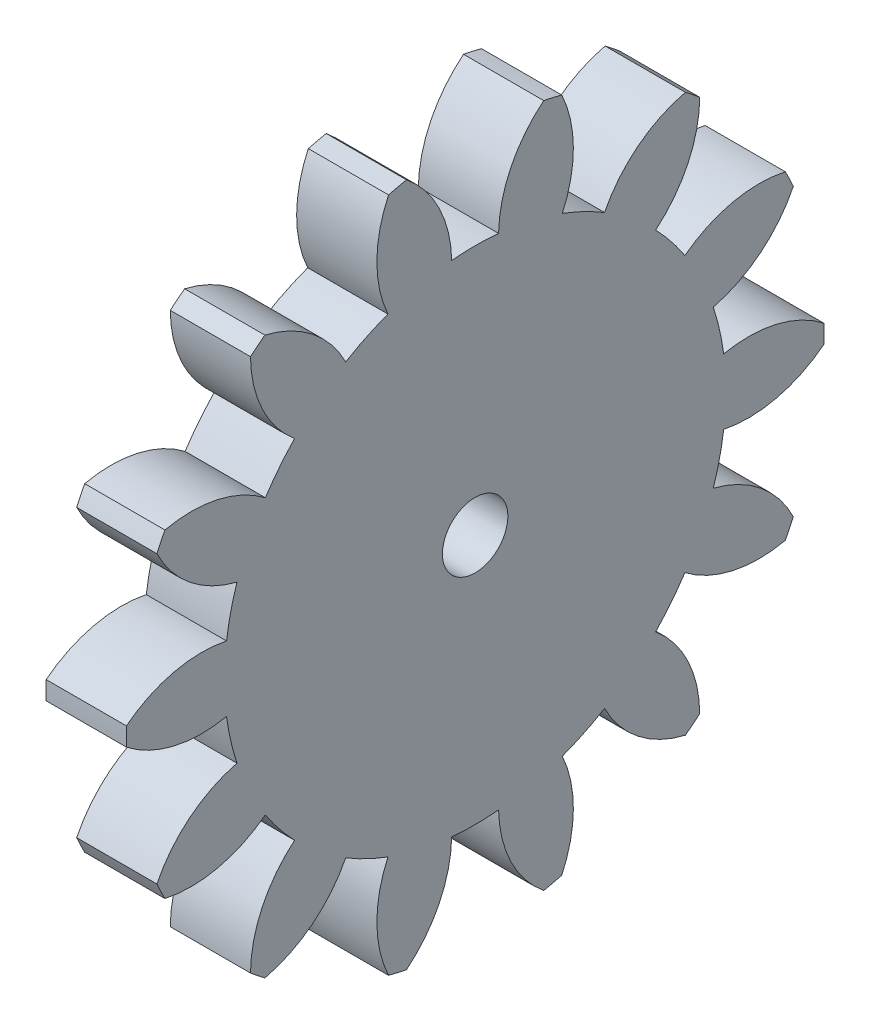
SolidWorks part; units mm, degrees
ref_plane "Plane1" through (0, 0, 0) normal (0, 0, 1) x (1, 0, 0)
ref_plane "Plane2" through (0, 0, 0) normal (0, 1, 0) x (1, 0, 0)
ref_plane "Plane3" through (0, 0, 0) normal (1, 0, 0) x (0, 0, -1)
sketch "HoldingSke" plane through (0, 0, 0) normal (0, 1, 0) x (1, 0, 0)
  line L0 (0, 0) -> (197.1641, -49.1585)
  line L1 (-15, 0) -> (100, 0) construction
  line L2 (0, 0) -> (-2.1039, 2.3779)
  line L3 (0, 0) -> (-11.863, 4.5341)
  line L4 (0, 0) -> (8.3795, 2.0892)
  line L5 (0, 0) -> (-47.5972, -17.7524)
  line L6 (0, 0) -> (-4.8428, -3.2675)
  line L7 (-2.1039, 2.3779) -> (8.8308, 51.9871)
  line L8 (-76.2, 54.61) -> (-71.1708, 54.61)
  line L9 (-71.009, 38.7566) -> (-53.1078, 45.2721)
  line L10 (-76.2, 71.12) -> (104.1128, 71.12)
  line L11 (0, 0) -> (-5.842, 0)
  line L12 (-76.2, 101.6) -> (-76.0857, 101.6)
  line L13 (24.9733, 27.94) -> (52.9518, 28.4284)
  line L14 (24.9733, 27.94) -> (24.9746, 27.94)
  line L15 (24.9733, 27.94) -> (100.4006, 29.5858)
  circle A0 centre (0, 0) radius 2.3812
  circle A1 centre (0, 0) radius 18.255
  circle A2 centre (0, 0) radius 38.1
  circle A3 centre (0, 0) radius 2.3812
  dimension "MHD" = 36.51
  dimension "Hub_dia" = 76.2
  dimension "Bore" = 4.7625
  dimension "MBD" = 4.7625
  dimension "Num_teeth" = 14
  dimension "Pitch" = 203.2
  dimension "Overall_len" = 50.8
  dimension "Show_teeth" = 14
  dimension "Thickness" = 5.842
  dimension "OAL" = 50.8001
  dimension "T_dim" = 5.0292
  dimension "Ap" = 20
  dimension "H" = 19.05
  dimension "Pitch_radius" = 180.3128
  dimension "Width" = 5.842
  dimension "Backlash" = 0.1143
  dimension "Addendum_fac" = 1
  dimension "Dedendum_fac" = 1.25
  dimension "Clearance_fac" = 0.25
  dimension "Dedendum_add" = 0.0013
sketch "BasProSke" plane through (0, 0, 0) normal (0, 1, 0) x (1, 0, 0)
  line L0 (-10, 0) -> (60, 0) construction
  line L1 (0, 0) -> (0, 25.4)
  line L2 (0, 0) -> (5.842, 0)
  line L3 (5.842, 0) -> (5.842, 25.4)
  line L4 (5.842, 25.4) -> (0, 25.4)
  dimension "Thickness" = 5.842
  dimension "Diameter" = 50.8
revolve "Base-Revolve" add sketch "BasProSke" angle 360 about L0
sketch "TooCutSke" plane through (0, 0, 0) normal (1, 0, 0) x (0, 0, -1)
  line L1 (0, 0) -> (0, 107) construction
  line L2 (0, 0) -> (-2.6882, 22.0618) construction
  line L3 (0, 0) -> (-9.8385, 43.1052) construction
  line L4 (-2.6882, 22.0618) -> (-4.9192, 21.5526) construction
  arc A0 (1.7067, 18.175) -> (-1.7067, 18.175) centre (0, 0) ccw
  arc A1 (5.0224, 24.9244) -> (-5.0224, 24.9244) centre (0, 0) ccw
  circle A2 centre (0, 0) radius 22.225 construction
  circle A3 centre (0, 0) radius 20.8847 construction
  arc A4 (-1.7067, 18.175) -> (-5.0224, 24.9244) centre (-10.5949, 17.9977) ccw
  arc A5 (5.0224, 24.9244) -> (1.7067, 18.175) centre (10.5949, 17.9977) ccw
  dimension "Root_dia" = 36.51
  dimension "Overcut_dia" = 50.8508
  dimension "Pitch_dia" = 44.45
  dimension "Base_dia" = 41.7693
  dimension "Flank_rad" = 8.89
  dimension "Half_ang" = 12.857
  dimension "Half_CT" = 2.2884
extrude "ToothCut" cut sketch "TooCutSke" along normal through all
fillet "Breaks" [suppressed] radius 0.0635
fillet "RootFillets" [suppressed] radius 0.795
pattern_circular "TeethCuts" count 14 every 25.714 about axis through (-10, 0, 0) along (1, 0, 0) of "ToothCut", "RootFillets", "Breaks"
sketch "HubNeaOneSke" plane through (0, 0, 0) normal (-1, 0, 0) x (0, 0, 1)
  circle A0 centre (0, 0) radius 18.255
  dimension "Diameter" = 36.51
extrude "HubNearOne" [suppressed] add sketch "HubNeaOneSke" along normal blind 44.9581
sketch "HubNeaBotSke" plane through (0, 0, 0) normal (-1, 0, 0) x (0, 0, 1)
  circle A0 centre (0, 0) radius 18.255
  dimension "Diameter" = 36.51
extrude "HubNearBoth" [suppressed] add sketch "HubNeaBotSke" along normal blind 22.479
ref_plane "FarPln" through (5.842, 0, 0) normal (1, 0, 0) x (0, 0, -1)
sketch "HubFarSke" plane through (5.842, 0, 0) normal (1, 0, 0) x (0, 0, -1)
  circle A0 centre (0, 0) radius 18.255
  dimension "Diameter" = 36.51
extrude "HubFar" [suppressed] add sketch "HubFarSke" along normal blind 22.479
sketch "BorSke" plane through (0, 0, 0) normal (1, 0, 0) x (0, 0, -1)
  circle A0 centre (0, 0) radius 2.3812
  dimension "Diameter" = 4.7625
extrude "Bore" cut sketch "BorSke" along normal mid plane 101.6001
sketch "KeySke" plane through (0, 0, 0) normal (1, 0, 0) x (0, 0, -1)
  line L0 (-0.127, 0) -> (-0.127, 2.6479)
  line L1 (-0.127, 2.6479) -> (0.127, 2.6479)
  line L2 (0.127, 2.6479) -> (0.127, 0)
  line L3 (0, 0) -> (0, 34) construction
  line L4 (-0.127, 0) -> (0.127, 0)
  dimension "Offset" = 2.648
  dimension "Width" = 0.254
extrude "Keyway" [suppressed] cut sketch "KeySke" along normal mid plane 101.6001
pattern_circular "Keyway2" [suppressed] count 2 every 90 about axis through (-10, 0, 0) along (1, 0, 0)
equation "' \"Pitch@HoldingSke\" = 4"
equation "' \"Num_teeth@HoldingSke\" = 12"
equation "' \"Ap@HoldingSke\" =  20"
equation "' \"Ap@HoldingSke\" = 20"
equation "' \"Width@HoldingSke\" = 0.5"
equation "' \"Hub_dia@HoldingSke\"= 1"
equation "' \"Hub_dia@HoldingSke\" = 1"
equation "' \"Overall_len@HoldingSke\" = 1.0"
equation "' \"Bore@HoldingSke\" = 0.75"
equation "' \"T_dim@HoldingSke\" = 0.85"
equation "' \"Width@KeySke\" = 0.25"
equation "' \"Show_teeth@HoldingSke\" = 13"
equation "' \"Backlash@HoldingSke\" = 0.009"
equation "' \"Addendum_fac@HoldingSke\" = 1.0"
equation "' \"Dedendum_fac@HoldingSke\" = 1.25"
equation "' \"Dedendum_add@HoldingSke\" = 0.00005"
equation "' \"Clearance_fac@HoldingSke\" = 0.25"
equation "' \"Pitch@HoldingSke\" = 0.5"
equation "' \"Num_teeth@HoldingSke\" = 23"
equation "' \"Show_teeth@HoldingSke\" = 23"
equation "' \"Backlash@HoldingSke\" = 0.0375"
equation "\"Overcut_dia@TooCutSke\" = (\"Num_teeth@HoldingSke\" + 2 * \"Addendum_fac@HoldingSke\") / \"Pitch@HoldingSke\" + 0.002"
equation "\"Pitch_dia@TooCutSke\" = \"Num_teeth@HoldingSke\" / \"Pitch@HoldingSke\""
equation "\"Base_dia@TooCutSke\" = \"Num_teeth@HoldingSke\" / \"Pitch@HoldingSke\" * cos((\"Ap@HoldingSke\"  * 3.14159265 / 180))"
equation "\"Root_dia@TooCutSke\" = (\"Num_teeth@HoldingSke\" + 2) / \"Pitch@HoldingSke\" - 2 * (\"Addendum_fac@HoldingSke\" + \"Dedendum_fac@HoldingSke\") / \"Pitch@HoldingSke\" - \"Dedendum_add@HoldingSke\" * 2"
equation "\"Half_ang@TooCutSke\" = 180 / \"Num_teeth@HoldingSke\""
equation "\"Half_CT@TooCutSke\" = \"Num_teeth@HoldingSke\" / \"Pitch@HoldingSke\" * sin((3.14159265 / 2 / \"Num_teeth@HoldingSke\")) / 2 - 7 * \"Backlash@HoldingSke\" / 4"
equation "\"Flank_rad@TooCutSke\" = \"Num_teeth@HoldingSke\" / \"Pitch@HoldingSke\" / 5"
equation "\"Radius@RootFillets\" = \"Clearance_fac@HoldingSke\" / \"Pitch@HoldingSke\" + \"Dedendum_add@HoldingSke\""
equation "\"Break_rad@Breaks\" = 0.02 / \"Pitch@HoldingSke\""
equation "\"Thickness@HoldingSke\" = \"Width@HoldingSke\""
equation "\"OAL@HoldingSke\" = \"Thickness@HoldingSke\""
equation "\"MHD@HoldingSke\" = (\"Num_teeth@HoldingSke\" + 2) / \"Pitch@HoldingSke\" - 2 * (\"Addendum_fac@HoldingSke\" + \"Dedendum_fac@HoldingSke\")  / \"Pitch@HoldingSke\" - \"Dedendum_add@HoldingSke\" * 2"
equation "\"MBD@HoldingSke\" = (\"Num_teeth@HoldingSke\" + 2) / \"Pitch@HoldingSke\" - 2 * (\"Addendum_fac@HoldingSke\" + \"Dedendum_fac@HoldingSke\")  / \"Pitch@HoldingSke\" - \"Dedendum_add@HoldingSke\" * 2 - 0.002"
equation "\"MHD@HoldingSke\" = ((sgn( \"MHD@HoldingSke\" - \"Hub_dia@HoldingSke\" )-1)*( \"MHD@HoldingSke\" - \"Hub_dia@HoldingSke\" ))/-2+ \"Hub_dia@HoldingSke\""
equation "\"MBD@HoldingSke\" = ((sgn( \"MBD@HoldingSke\" - \"Bore@HoldingSke\" )-1)*( \"MBD@HoldingSke\" - \"Bore@HoldingSke\" ))/-2+ \"Bore@HoldingSke\""
equation "\"OAL@HoldingSke\" = ((sgn( \"OAL@HoldingSke\" - \"Overall_len@HoldingSke\" )+1)*( \"OAL@HoldingSke\" - \"Overall_len@HoldingSke\" ))/2 + \"Overall_len@HoldingSke\" + 0.000002"
equation "\"Num_teeth@TeethCuts\" = int( \"Show_teeth@HoldingSke\" ) + 1"
equation "\"Num_teeth@TeethCuts\" = ((sgn( \"Num_teeth@TeethCuts\" - \"Num_teeth@HoldingSke\" )-1)*( \"Num_teeth@TeethCuts\" - \"Num_teeth@HoldingSke\" ))/-2+ \"Num_teeth@HoldingSke\""
equation "\"Num_teeth@TeethCuts\" = ((sgn( \"Num_teeth@TeethCuts\" - 2.0)+1)*( \"Num_teeth@TeethCuts\" - 2.0))/2 +2.0"
equation "\"Angle@TeethCuts\" = 360.0 / \"Num_teeth@HoldingSke\""
equation "\"Diameter@BasProSke\" = (\"Num_teeth@HoldingSke\" + 2 * \"Addendum_fac@HoldingSke\") / \"Pitch@HoldingSke\""
equation "\"Thickness@BasProSke\"  = \"Thickness@HoldingSke\""
equation "' \"Fillet_rad@BasProSke\" =  \"Thickness@HoldingSke\" * 0.05"
equation "' \"Fillet_rad@BasProSke\" = \"Thickness@HoldingSke\" * 0.05"
equation "\"MHD@HoldingSke\" = ((sgn( \"MHD@HoldingSke\" - \"Root_dia@TooCutSke\" )-1)*( \"MHD@HoldingSke\" - \"Root_dia@TooCutSke\" ))/-2+ \"Root_dia@TooCutSke\""
equation "\"Diameter@HubNeaOneSke\" = \"MHD@HoldingSke\""
equation "\"Length@HubNearOne\" = \"OAL@HoldingSke\" - \"Thickness@BasProSke\""
equation "\"Diameter@HubNeaBotSke\" = \"MHD@HoldingSke\""
equation "\"Length@HubNearBoth\" = ( \"OAL@HoldingSke\" - \"Thickness@BasProSke\" ) / 2.0"
equation "\"Thickness@FarPln\" = \"Thickness@BasProSke\""
equation "\"Diameter@HubFarSke\" = \"MHD@HoldingSke\""
equation "\"Length@HubFar\" = ( \"OAL@HoldingSke\" - \"Thickness@BasProSke\" ) / 2.0"
equation "\"Diameter@BorSke\" = \"MBD@HoldingSke\""
equation "\"D1@Bore\" = \"OAL@HoldingSke\" * 2.0"
equation "\"D1@Keyway\" = \"OAL@HoldingSke\" * 2.0"
equation "\"Offset@KeySke\" = \"T_dim@HoldingSke\" - \"MBD@HoldingSke\" / 2.0"
